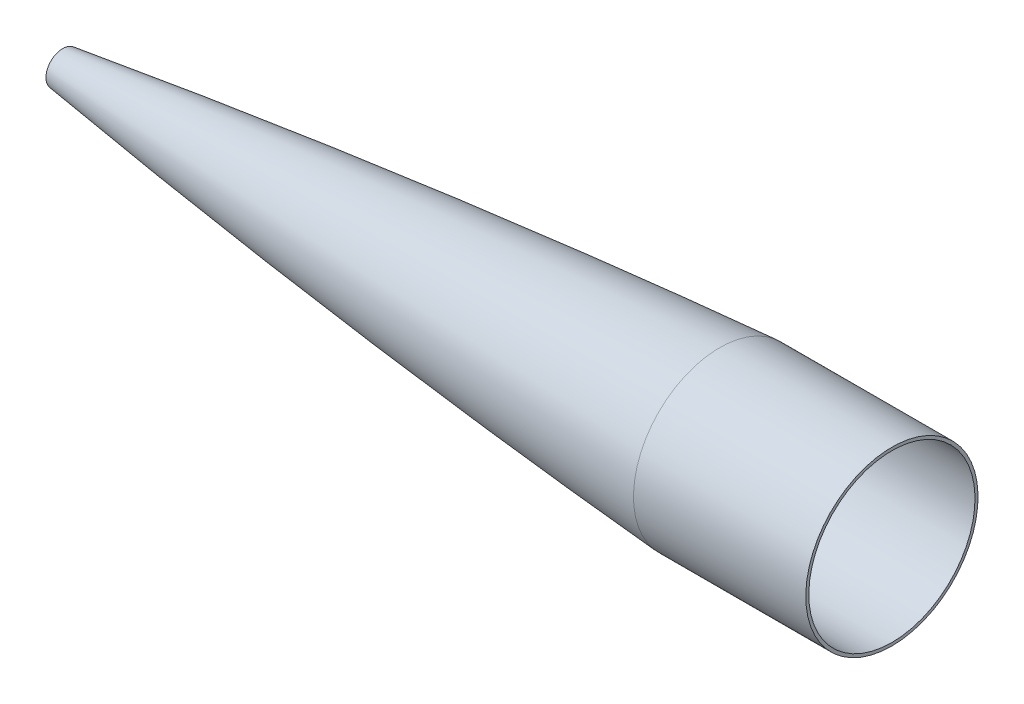
SolidWorks part; units mm, degrees
material "PVC 0.007 Plasticized"
ref_plane "Płaszczyzna przednia" through (0, 0, 0) normal (0, 0, 1) x (1, 0, 0)
ref_plane "Płaszczyzna górna" through (0, 0, 0) normal (0, 1, 0) x (1, 0, 0)
ref_plane "Płaszczyzna prawa" through (0, 0, 0) normal (1, 0, 0) x (0, 0, -1)
ref_plane "Plane1" through (0, 0, 0) normal (0, 0, -1) x (-1, 0, 0)
sketch "Sketch1" plane through (0, 0, 0) normal (0, 0, -1) x (-1, 0, 0)
  line L2 (-763.2353, 0) -> (0, 0) construction
  line L8 (-763.3824, 85) -> (-763.2353, 85)
  line L13 (-763.3824, 82) -> (-763.3458, 82)
  line L14 (-763.3824, 85) -> (-763.3824, 82)
  line L15 (0, 0) -> (-22.4653, 0)
  line L16 (-22.4653, 0) -> (-22.4653, 0.2965)
  arc A0 (0, 0) -> (-763.2353, 85) centre (-1520.6726, -10185.346) ccw
  arc A4 (-22.4653, 0.2965) -> (-763.3458, 82) centre (-1520.6726, -10185.346) ccw
  arc A5 (-0.443, -2.9671) -> (-763.3458, 82) centre (-1520.6726, -10185.346) ccw construction
  dimension "D1" = 85
  dimension "D2" = 3
revolve "Revolve1" add sketch "Sketch1" angle 360 about L2
sketch "Sketch14" plane through (0, 0, 0) normal (0, 0, -1) x (-1, 0, 0)
  line L1 (-763.2353, 0) -> (-933.2353, 0) construction
  line L2 (-933.2353, 0) -> (-933.2353, 85) construction
  line L12 (-763.3824, 85) -> (-933.2353, 85)
  line L13 (-763.3824, 85) -> (-763.2353, 82)
  line L14 (-763.2353, 82) -> (-933.2353, 82)
  line L15 (-933.2353, 82) -> (-933.2353, 85)
  dimension "D1" = 3
revolve "Revolve4" add sketch "Sketch14" angle 360 about L1
sketch "Sketch16" plane through (0, 0, 0) normal (0, 0, 1) x (1, 0, 0)
  line L18 (763.1248, 88) -> (753.3824, 77.2491)
  line L20 (97.5171, 0) -> (789.3389, 0) construction
  line L24 (107.5171, 8.4062) -> (107.5171, 18.5017)
  line L25 (763.2353, 85) -> (933.2353, 85)
  line L27 (933.2353, 85) -> (933.2353, -85)
  line L28 (763.2353, 85) -> (933.2353, 85)
  line L29 (933.2353, 85) -> (933.2353, -85)
  line L30 (933.2353, -85) -> (763.2353, -85)
  line L31 (933.2353, -85) -> (763.2353, -85)
  arc A4 (753.3824, 77.2491) -> (107.5171, 8.4062) centre (1520.6726, -10185.346) ccw
  arc A9 (0, 0) -> (763.2353, -85) centre (1520.6726, 10185.346) ccw
  arc A10 (763.2353, 85) -> (0, 0) centre (1520.6726, -10185.346) ccw
  arc A11 (0, 0) -> (763.2353, -85) centre (1520.6726, 10185.346) ccw
  arc A12 (763.2353, 85) -> (0, 0) centre (1520.6726, -10185.346) ccw
sketch "Sketch18" plane through (0, 0, 0) normal (0, 0, 1) x (1, 0, 0)
  line L2 (-14.4563, 18.5017) -> (-14.4563, -44.1703)
  line L9 (0, 0) -> (115, 0)
  line L10 (115, 0) -> (115, 28.1932)
  line L11 (115, 28.1932) -> (-14.4563, 28.1932)
  line L12 (-14.4563, 28.1932) -> (-14.4563, 18.5017)
  line L13 (-14.4563, -44.1703) -> (115, -44.1703)
  line L14 (115, -44.1703) -> (115, 0)
extrude "Cut-Extrude3" cut sketch "Sketch18" against normal mid plane 500
sketch "Sketch19" plane through (0, 0, 0) normal (0, 0, 1) x (1, 0, 0)
  line L0 (115, 16.5069) -> (115, 0)
  line L1 (115, 16.5069) -> (115, -16.5069) construction
  line L2 (115, 0) -> (124.8, 0)
  line L3 (115, 16.5069) -> (124.8, 17.5054)
  line L4 (124.8, 17.5054) -> (124.8, 0)
revolve "Revolve6" add sketch "Sketch19" angle 360 about L2
sketch "Sketch20" plane through (115, 0, 0) normal (-1, 0, 0) x (0, 0, 1)
  circle A0 centre (0, 0) radius 3
  dimension "D1" = 6
extrude "Cut-Extrude4" cut sketch "Sketch20" against normal mid plane 500
sketch "Sketch21" plane through (0, 0, 0) normal (0, 0, 1) x (1, 0, 0)
  line L0 (115, -16.5069) -> (115, 16.5069)
  line L2 (763.2353, 85) -> (933.2353, 85)
  line L4 (933.2353, 85) -> (933.2353, -85)
  line L6 (933.2353, -85) -> (763.2353, -85)
  line L12 (763.2353, 85) -> (933.2353, 85) construction
  line L13 (763.6036, 75) -> (923.2353, 75) construction
  line L14 (923.2353, 75) -> (923.2353, -75) construction
  line L15 (933.2353, 85) -> (933.2353, -85) construction
  line L16 (923.2353, -75) -> (763.6036, -75) construction
  line L17 (933.2353, -85) -> (763.2353, -85) construction
  line L18 (125, -7.7866) -> (125, 7.7866) construction
  line L19 (115, -16.5069) -> (115, 16.5069) construction
  line L20 (115, 0) -> (776.9072, 0) construction
  line L21 (763.2353, 85) -> (763.6036, 75)
  line L22 (125, 7.7866) -> (115, 7.0442)
  line L23 (115, 16.5069) -> (115, -16.5069) construction
  line L24 (115, 16.5069) -> (115, 7.0442)
  arc A0 (763.2353, 85) -> (115, 16.5069) centre (1520.6726, -10185.346) ccw
  arc A1 (763.2353, 85) -> (115, 16.5069) centre (1520.6726, -10185.346) ccw
  arc A2 (115, -16.5069) -> (763.2353, -85) centre (1520.6726, 10185.346) ccw
  arc A4 (763.6036, 75) -> (125, 7.7866) centre (1520.6726, -10185.346) ccw
  arc A6 (125, -7.7866) -> (763.6036, -75) centre (1520.6726, 10185.346) ccw construction
  arc A7 (115, -16.5069) -> (763.2353, -85) centre (1520.6726, 10185.346) ccw construction
  dimension "D1" = 10
revolve "Revolve7" add sketch "Sketch21" angle 5 about L20
pattern_circular "CirPattern2" count 14 over 360 about axis through (0, 0, 0) along (1, 0, 0) of "Revolve7"
